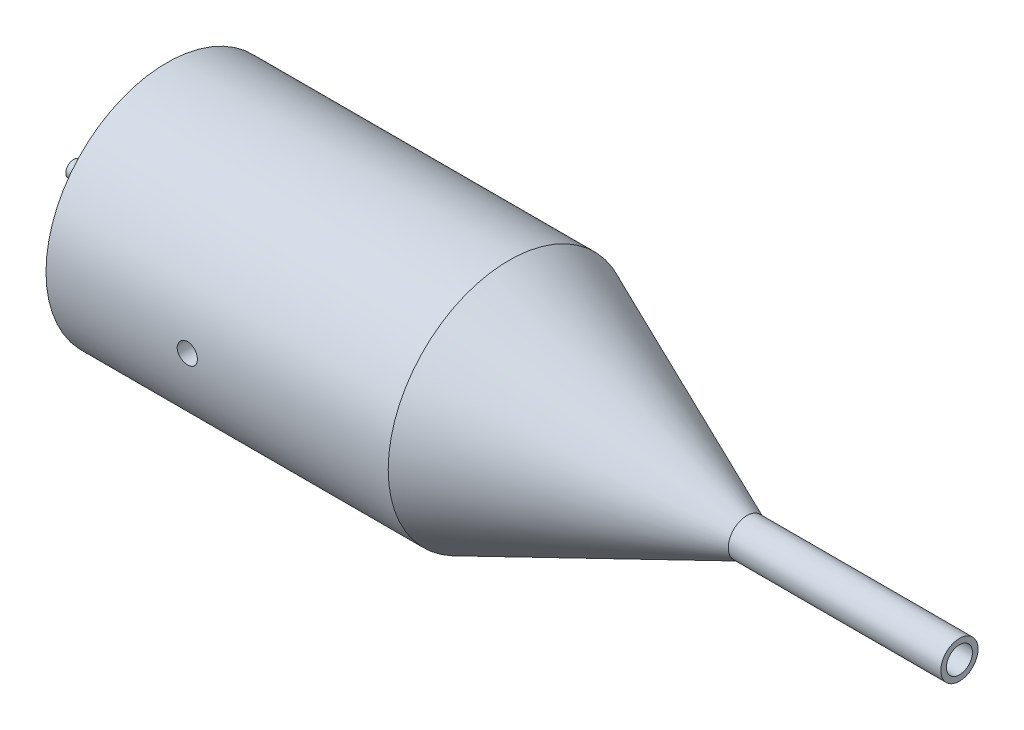
SolidWorks part; units mm, degrees
ref_plane "Plano frontal" through (0, 0, 0) normal (0, 0, 1) x (1, 0, 0)
ref_plane "Plano superior" through (0, 0, 0) normal (0, 1, 0) x (1, 0, 0)
ref_plane "Plano direito" through (0, 0, 0) normal (1, 0, 0) x (0, 0, -1)
sketch "Esboço1" plane through (0, 0, 0) normal (0, 0, 1) x (1, 0, 0)
  line L0 (0, 0) -> (9, 0) construction
  line L1 (9, 0) -> (9, -32.5)
  line L2 (9, -32.5) -> (101, -32.5)
  line L3 (7.1889, 0) -> (164.9199, 0) construction
  line L4 (101, -32.5) -> (101, 0) construction
  line L7 (164.9199, -4.9996) -> (101, -32.5)
  line L8 (164.9199, -4.9996) -> (222.0739, -4.9996)
  line L9 (222.0739, -4.9996) -> (222.0739, 0)
  line L10 (222.0739, 0) -> (164.9199, 0)
  line L11 (9, 0) -> (164.9199, 0)
  dimension "D1" = 9
  dimension "D2" = 32.5
  dimension "D3" = 92
revolve "Revolução1" add sketch "Esboço1" angle 360 about L11
sketch "Esboço2" plane through (9, 0, 0) normal (-1, 0, 0) x (0, 0, 1)
  circle A2 centre (0, 0) radius 12.8 construction
  circle A3 centre (0, 12.8) radius 2.1
  circle A4 centre (11.0851, 6.4) radius 2.1
  circle A5 centre (11.0851, -6.4) radius 2.1
  circle A6 centre (0, -12.8) radius 2.1
  circle A7 centre (-11.0851, -6.4) radius 2.1
  circle A8 centre (-11.0851, 6.4) radius 2.1
  point P19 (0, 0)
  dimension "D1" = 25.6
  dimension "D3" = 4.2
  dimension "D4" = 6
extrude "Ressalto-extrusão1" add sketch "Esboço2" along normal blind 14
sketch "Esboço3" plane through (9, 0, 0) normal (-1, 0, 0) x (0, 0, 1)
  circle A0 centre (0, 0) radius 10
  dimension "D1" = 20
extrude "Ressalto-extrusão2" add sketch "Esboço3" along normal blind 5
sketch "Esboço4" plane through (222.0739, 0, 0) normal (1, 0, 0) x (0, 0, -1)
  circle A0 centre (0, 0) radius 3.502
extrude "Corte-extrusão1" cut sketch "Esboço4" against normal blind 195
sketch "Esboço5" plane through (0, 0, 0) normal (0, 0, 1) x (1, 0, 0)
  circle A0 centre (46.9802, 0) radius 2.71
extrude "Corte-extrusão2" cut sketch "Esboço5" along normal blind 45
